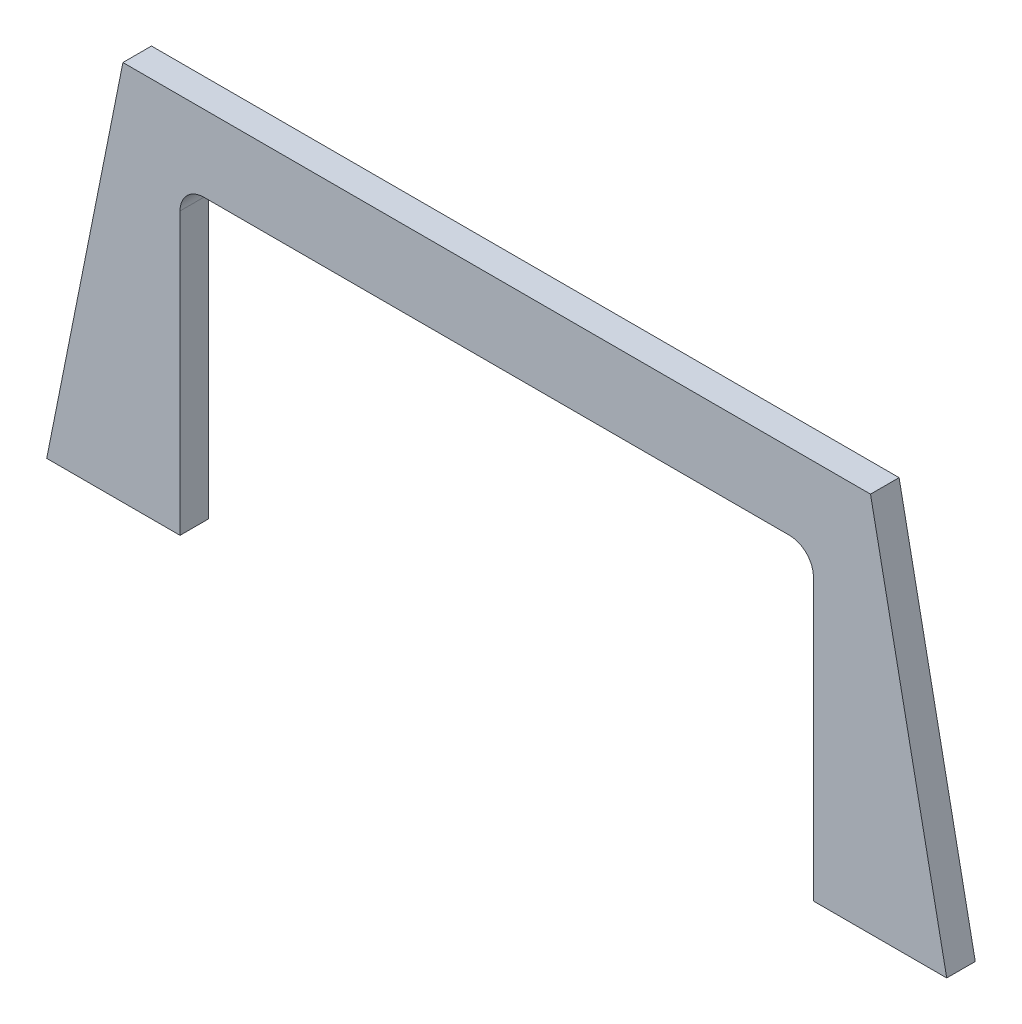
SolidWorks part; units mm, degrees
material "MDF"
ref_plane "Plano frontal" through (0, 0, 0) normal (0, 0, 1) x (1, 0, 0)
ref_plane "Plano superior" through (0, 0, 0) normal (0, 1, 0) x (1, 0, 0)
ref_plane "Plano direito" through (0, 0, 0) normal (1, 0, 0) x (0, 0, -1)
sketch "Esboço1" plane through (0, 0, 0) normal (0, 0, 1) x (1, 0, 0)
  line L0 (-66.5, -40) -> (-94.5, -40)
  line L1 (94.5, -40) -> (66.5, -40)
  line L2 (0, -54.8769) -> (0, 67.5991) construction
  line L3 (-78.5, 40) -> (78.5, 40)
  line L7 (-78.5, 40) -> (-94.5, -40)
  line L8 (66.5, -40) -> (66.5, 19)
  line L9 (61.5, 24) -> (-61.5, 24)
  line L10 (-66.5, -40) -> (-66.5, 19)
  line L12 (78.5, 40) -> (94.5, -40)
  arc A0 (61.5, 24) -> (66.5, 19) centre (61.5, 19) cw
  arc A1 (-61.5, 24) -> (-66.5, 19) centre (-61.5, 19) ccw
  point P4 (66.5, 24)
  point P11 (-66.5, 24)
  dimension "D2" = 5
  dimension "D1" = 189
  dimension "D3" = 133
  dimension "D5" = 94.5
extrude "Ressalto-extrusão1" add sketch "Esboço1" along normal blind 6
